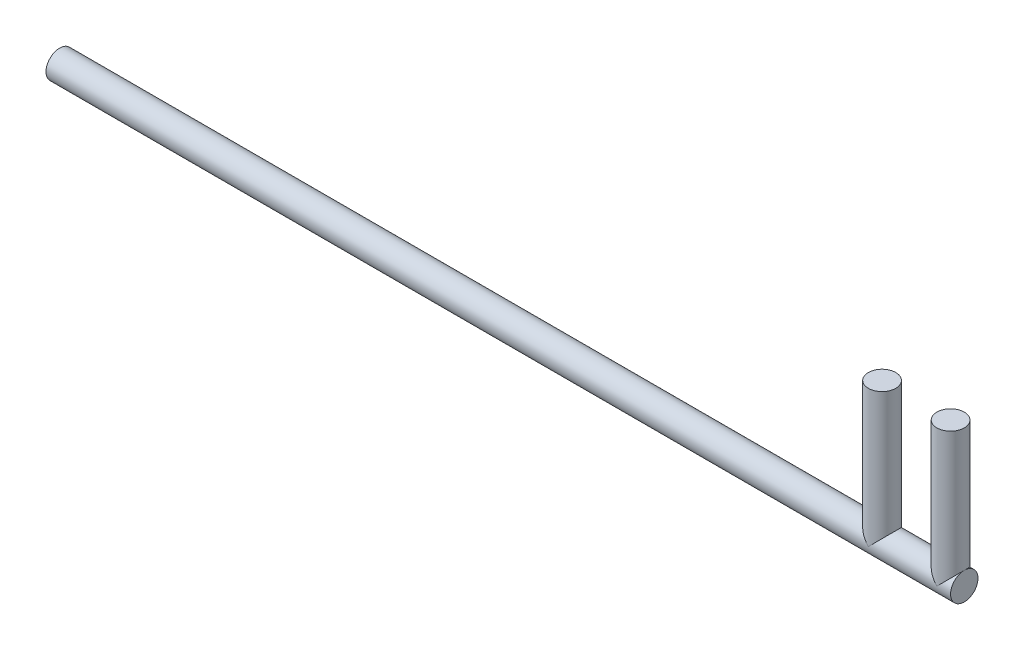
SolidWorks part; units mm, degrees
material "AISI 1020"
ref_plane "Plano frontal" through (0, 0, 0) normal (0, 0, 1) x (1, 0, 0)
ref_plane "Plano superior" through (0, 0, 0) normal (0, 1, 0) x (1, 0, 0)
ref_plane "Plano direito" through (0, 0, 0) normal (1, 0, 0) x (0, 0, -1)
sketch "Esboço1" plane through (0, 0, 0) normal (0, 0, 1) x (1, 0, 0)
  line L0 (8.3407, 0) -> (5.8407, 0)
  line L1 (8.3407, 0) -> (8.3407, 5)
  line L2 (5.8407, 0) -> (5.8407, 5)
  dimension "D3" = 2.5
  dimension "D4" = 5
  dimension "D5" = 5
sweep "Varredura1" add path "Esboço1" circular profile diameter 1 parameters "D3"=1
sketch "Esboço37" plane through (0, 0, 0) normal (0, 0, 1) x (1, 0, 0)
  line L0 (8.8407, 0) -> (-24.1593, 0)
  line L1 (8.8407, -0.5) -> (8.8407, 5) construction
  dimension "D1" = 33
sweep "Varredura2" add path "Esboço37" circular profile diameter 1 parameters "D3"=1
